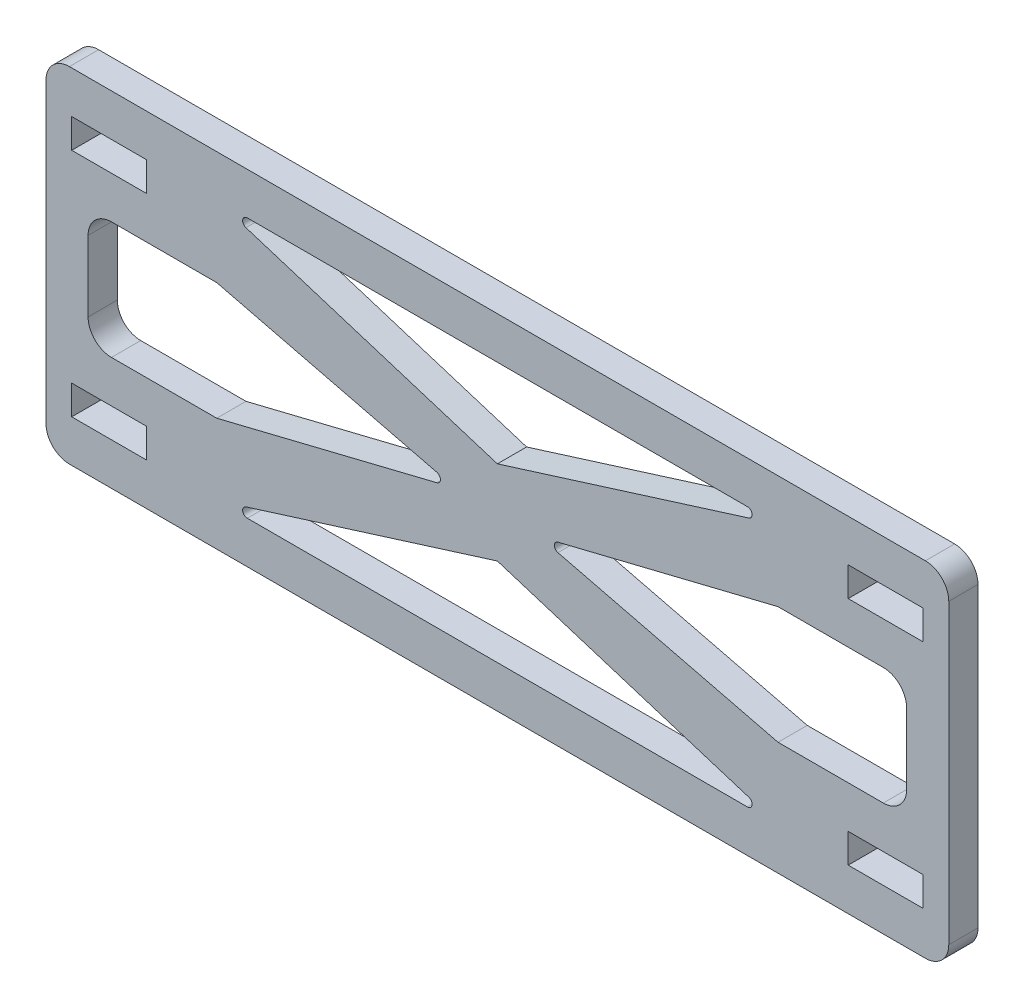
SolidWorks part; units mm, degrees
ref_plane "Front Plane" through (0, 0, 0) normal (0, 0, 1) x (1, 0, 0)
ref_plane "Top Plane" through (0, 0, 0) normal (0, 1, 0) x (1, 0, 0)
ref_plane "Right Plane" through (0, 0, 0) normal (1, 0, 0) x (0, 0, -1)
sketch "Sketch1" plane through (0, 0, 56.9471) normal (0, 0, 1) x (1, 0, 0)
  line L0 (32.315, 33.4941) -> (32.315, 35.0816) construction
  line L1 (30.283, 33.4941) -> (33.458, 33.4941)
  line L2 (30.283, 33.4941) -> (30.283, 35.0816)
  line L3 (33.458, 35.0816) -> (30.283, 35.0816)
  line L4 (33.458, 33.4941) -> (33.458, 35.0816) construction
  line L5 (32.315, 35.0816) -> (32.315, 33.4941) construction
  line L6 (32.315, 35.0816) -> (32.315, 33.4941) construction
  line L7 (-7.817, 33.4941) -> (30.283, 33.4941) construction
  line L8 (28.505, 20.9592) -> (30.283, 20.9592) construction
  line L9 (35.744, 18.6732) -> (-13.278, 18.6732)
  line L10 (35.744, 18.6732) -> (35.744, 37.3676)
  line L11 (35.744, 37.3676) -> (-13.278, 37.3676)
  line L12 (-13.278, 18.6732) -> (-13.278, 37.3676)
  line L13 (30.283, 20.9592) -> (30.283, 22.5467) construction
  line L14 (29.7261, 20.9592) -> (29.7261, 18.6732) construction
  line L15 (30.283, 20.9592) -> (-7.817, 20.9592) construction
  line L16 (29.3715, 35.0816) -> (29.3715, 37.3676) construction
  line L17 (-7.817, 35.0816) -> (30.283, 35.0816) construction
  line L18 (30.283, 21.392) -> (35.744, 21.392) construction
  line L19 (-7.817, 20.9592) -> (-7.817, 22.5467) construction
  line L20 (-7.817, 21.2824) -> (-13.278, 21.2824) construction
  line L21 (11.233, 18.6732) -> (11.233, 37.3676) construction
  line L22 (35.744, 28.0204) -> (-13.278, 28.0204) construction
  line L23 (30.283, 35.0816) -> (30.2891, 35.0677)
  line L24 (31.172, 35.0816) -> (34.347, 35.0816)
  line L25 (34.347, 35.0816) -> (34.347, 33.4941)
  line L26 (34.347, 33.4941) -> (31.172, 33.4941)
  line L27 (30.283, 33.4941) -> (33.458, 33.4941)
  line L29 (33.458, 35.0816) -> (30.283, 35.0816)
  line L30 (33.458, 33.4941) -> (33.458, 35.0816) construction
  line L32 (-7.817, 35.0816) -> (-7.817, 33.4941)
  line L33 (-10.992, 35.0816) -> (-7.817, 35.0816)
  line L34 (-7.817, 33.4941) -> (-10.992, 33.4941)
  line L35 (-8.706, 35.0816) -> (-11.881, 35.0816)
  line L36 (-11.881, 35.0816) -> (-11.881, 33.4941)
  line L37 (-11.881, 33.4941) -> (-8.706, 33.4941)
  line L38 (-11.881, 22.5467) -> (-8.706, 22.5467)
  line L39 (-11.881, 20.9592) -> (-11.881, 22.5467)
  line L40 (-8.706, 20.9592) -> (-11.881, 20.9592)
  line L41 (-10.992, 20.9592) -> (-7.817, 20.9592)
  line L42 (-7.817, 20.9592) -> (-7.817, 22.5467)
  line L43 (-7.817, 22.5467) -> (-10.992, 22.5467)
  line L44 (34.347, 22.5467) -> (31.172, 22.5467)
  line L45 (34.347, 20.9592) -> (34.347, 22.5467)
  line L46 (31.172, 20.9592) -> (34.347, 20.9592)
  line L47 (33.458, 20.9592) -> (30.283, 20.9592)
  line L48 (30.283, 20.9592) -> (30.283, 22.5467)
  line L49 (30.283, 22.5467) -> (33.458, 22.5467)
  line M1 (-7.817, 33.4941) -> (30.283, 33.4941)
  line M2 (30.283, 33.4941) -> (30.283, 35.0816)
  line M3 (30.283, 35.0816) -> (-7.817, 35.0816)
  line M4 (-7.817, 35.0816) -> (-7.817, 33.4941)
  dimension "D1" = 3.175
  dimension "D2" = 1.5875
  dimension "D3" = 2.032
  dimension "D4" = 2.286
  dimension "D5" = 2.286
extrude "Boss-Extrude1" add sketch "Sketch1" along normal blind 1.5875 contours L12 L9 L10 L11 L37 L36 L35 L33 L3 L24 L25 L26 L1 L34 L43 L42 L41 L40 L39 L38 L48 L49 L44 L45 L46 L47 M3 M1 | M4 M1 M2 M3
sketch "Sketch3" plane through (0, 0, 58.5346) normal (0, 0, 1) x (1, 0, 0)
  line L0 (-4.0069, 35.0816) -> (26.4729, 35.0816)
  line L1 (26.4729, 35.0816) -> (11.233, 30.3064)
  line L2 (11.233, 30.3064) -> (-4.0069, 35.0816)
  line L3 (11.233, 37.3676) -> (11.233, 18.4192) construction
  line L4 (35.744, 37.3676) -> (-13.278, 37.3676) construction
  line L5 (35.744, 18.6732) -> (35.744, 37.3676) construction
  line L6 (-7.817, 20.9592) -> (-7.817, 22.5467) construction
  line L7 (-6.2929, 35.0816) -> (-6.2929, 33.4941) construction
  line L9 (-7.817, 20.9592) -> (-7.817, 22.5467)
  line L10 (-13.532, 28.0204) -> (35.744, 28.0204) construction
  line L13 (26.4729, 20.9592) -> (11.233, 25.7344)
  line L14 (11.233, 25.7344) -> (-4.0069, 20.9592)
  line L15 (-4.0069, 20.9592) -> (26.4729, 20.9592)
  line L16 (-4.0069, 31.2081) -> (-10.992, 31.2081)
  line L17 (-4.0069, 24.8327) -> (8.947, 28.0204)
  line L18 (8.947, 28.0204) -> (-4.0069, 31.2081)
  line L20 (-4.0069, 24.8327) -> (-10.992, 24.8327)
  line L21 (-10.992, 31.2081) -> (-10.992, 24.8327)
  line L22 (26.4729, 24.8327) -> (33.458, 24.8327)
  line L23 (33.458, 31.2081) -> (33.458, 24.8327)
  line L24 (26.4729, 31.2081) -> (33.458, 31.2081)
  line L25 (26.4729, 24.8327) -> (13.519, 28.0204)
  line L26 (13.519, 28.0204) -> (26.4729, 31.2081)
  line L27 (-13.278, 18.6732) -> (-13.278, 37.3676) construction
  line L28 (-11.881, 33.4941) -> (-7.817, 33.4941) construction
  point P9 (11.233, 35.0816)
  dimension "D1" = 2.286
  dimension "D2" = 2.286
  dimension "D3" = 2.286
  dimension "D4" = 2.286
  dimension "D5" = 2.286
  dimension "D6" = 2.286
extrude "Cut-Extrude1" cut sketch "Sketch3" against normal up to next contours L14 L15 L13 | L26 L25 L22 L23 L24 | L2 L1 L0 | L16 L21 L20 L17 L18
fillet "Fillet1" radius 0.254 6 edges at (26.4729, 35.0816, 57.7409) (-4.0069, 35.0816, 57.7409) (-4.0069, 20.9592, 57.7409) (26.4729, 20.9592, 57.7409) (8.947, 28.0204, 57.7409) (13.519, 28.0204, 57.7409)
fillet "Fillet2" radius 1.27 8 edges at (33.458, 24.8327, 57.7409) (33.458, 31.2081, 57.7409) (-10.992, 31.2081, 57.7409) (-10.992, 24.8327, 57.7409) (-13.278, 18.6732, 57.7409) (-13.278, 37.3676, 57.7409) (35.744, 37.3676, 57.7409) (35.744, 18.6732, 57.7409)
